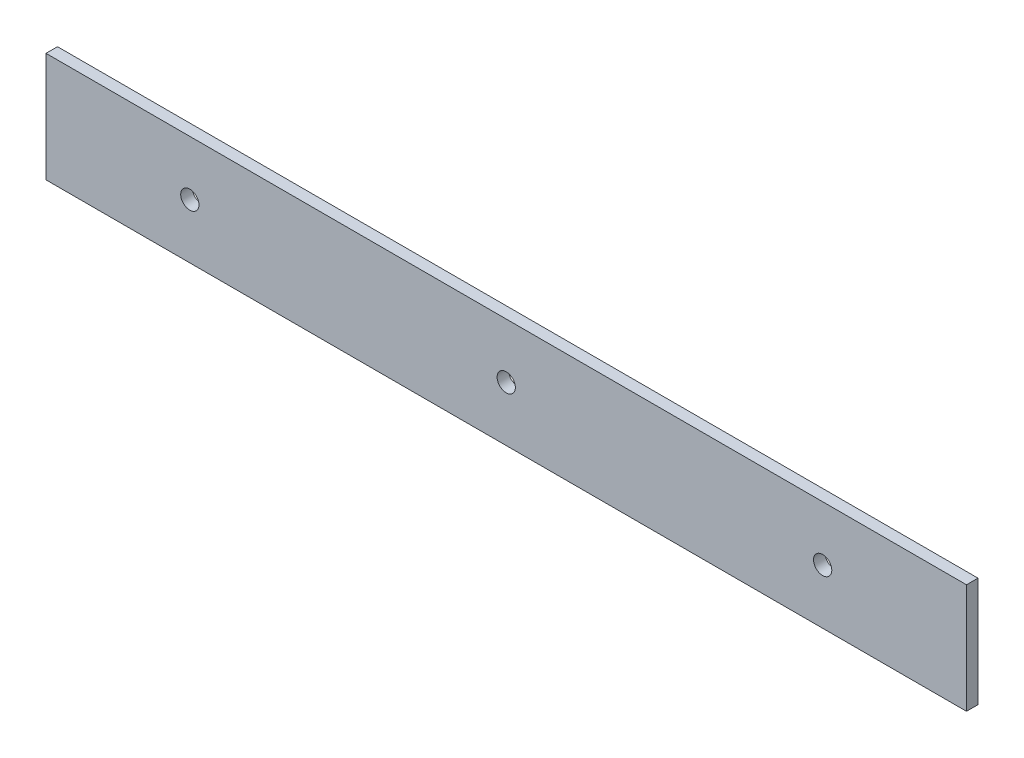
SolidWorks part; units mm, degrees
ref_plane "Alzado" through (0, 0, 0) normal (0, 0, 1) x (1, 0, 0)
ref_plane "Planta" through (0, 0, 0) normal (0, 1, 0) x (1, 0, 0)
ref_plane "Vista lateral" through (0, 0, 0) normal (1, 0, 0) x (0, 0, -1)
sketch "Croquis1" plane through (0, 0, 0) normal (0, 0, 1) x (1, 0, 0)
  line L1 (160, -19.05) -> (-160, -19.05)
  line L2 (160, -19.05) -> (160, 19.05)
  line L3 (160, 19.05) -> (-160, 19.05)
  line L4 (-160, -19.05) -> (-160, 19.05)
  line L5 (160, -19.05) -> (-160, 19.05) construction
  line L6 (160, 19.05) -> (-160, -19.05) construction
  point P0 (0, 0)
  dimension "D1" = 320
  dimension "D2" = 38.1
extrude "Saliente-Extruir1" add sketch "Croquis1" along normal blind 4
sketch "Croquis2" plane through (0, 0, 4) normal (0, 0, 1) x (1, 0, 0)
  line L0 (0, 0) -> (110, 0) construction
  line L1 (0, 10.1222) -> (0, -15.637) construction
  circle A0 centre (110, 0) radius 3.175
  circle A1 centre (0, 0) radius 3.175
  circle A2 centre (-110, 0) radius 3.175
  dimension "D2" = 6.35
  dimension "D3" = 6.35
  dimension "D1" = 110
extrude "Cortar-Extruir1" cut sketch "Croquis2" against normal blind 10
